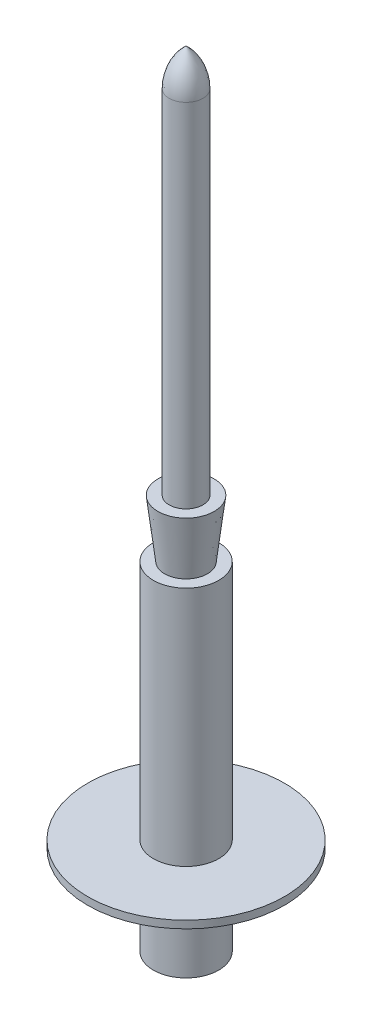
SolidWorks part; units mm, degrees
ref_plane "Front Plane" through (0, 0, 0) normal (0, 0, 1) x (1, 0, 0)
ref_plane "Top Plane" through (0, 0, 0) normal (0, 1, 0) x (1, 0, 0)
ref_plane "Right Plane" through (0, 0, 0) normal (1, 0, 0) x (0, 0, -1)
sketch "Sketch1" plane through (0, 0, 0) normal (0, 0, 1) x (1, 0, 0)
  line L0 (0, 0) -> (2.9, 0)
  line L2 (2.9, 29.97) -> (1.9, 29.97)
  line L5 (1.5, 35.07) -> (1.5, 66.3238)
  line L6 (0, 69.5986) -> (0, 0) construction
  line L8 (2.9, 0) -> (2.9, 7.9)
  line L9 (2.9, 7.9) -> (8.7329, 7.9)
  line L10 (8.7329, 7.9) -> (8.7329, 8.57)
  line L11 (8.7329, 8.57) -> (2.9, 8.57)
  line L12 (2.9, 8.57) -> (2.9, 29.97)
  line L13 (1.9, 29.97) -> (2.5, 35.07)
  line L14 (2.5, 35.07) -> (1.5, 35.07)
  line L15 (0, 69.5986) -> (0, 0)
  arc A0 (1.5, 66.3238) -> (0, 69.5986) centre (-2.8247, 66.3238) ccw
  dimension "D1" = 7.9
  dimension "D2" = 0.67
  dimension "D3" = 21.4
  dimension "D4" = 1
  dimension "D5" = 1
  dimension "D6" = 5.1
  dimension "D7" = 1.5
  dimension "D8" = 2.9
  dimension "D9" = 2.9
revolve "Revolve1" add sketch "Sketch1" angle 360 about L15
